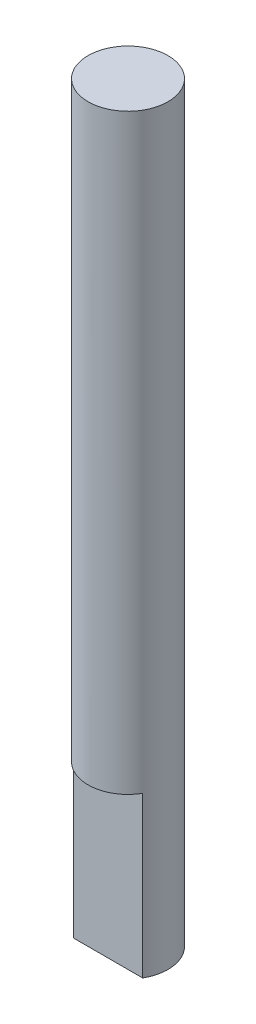
SolidWorks part; units mm, degrees
ref_plane "Płaszczyzna przednia" through (0, 0, 0) normal (0, 0, 1) x (1, 0, 0)
ref_plane "Płaszczyzna górna" through (0, 0, 0) normal (0, 1, 0) x (1, 0, 0)
ref_plane "Płaszczyzna prawa" through (0, 0, 0) normal (1, 0, 0) x (0, 0, -1)
sketch "Szkic1" plane through (0, 0, 0) normal (0, 1, 0) x (1, 0, 0)
  circle A0 centre (0, 0) radius 5
  dimension "D1" = 10
extrude "Dodanie-wyciągnięcie1" add sketch "Szkic1" along normal blind 94
sketch "Szkic2" plane through (0, 0, 0) normal (0, -1, 0) x (1, 0, 0)
  line L1 (5.4813, 7.5) -> (-5.4813, 7.5)
  line L2 (5.4813, 7.5) -> (5.4813, 2.5)
  line L3 (5.4813, 2.5) -> (-5.4813, 2.5)
  line L4 (-5.4813, 7.5) -> (-5.4813, 2.5)
  line L5 (5.4813, 7.5) -> (-5.4813, 2.5) construction
  line L6 (5.4813, 2.5) -> (-5.4813, 7.5) construction
  circle A0 centre (0, 0) radius 5 construction
  point P0 (0, 5)
  dimension "D1" = 5
  dimension "D2" = 10.9625
extrude "Wytnij-wyciągnięcie1" cut sketch "Szkic2" against normal blind 20
